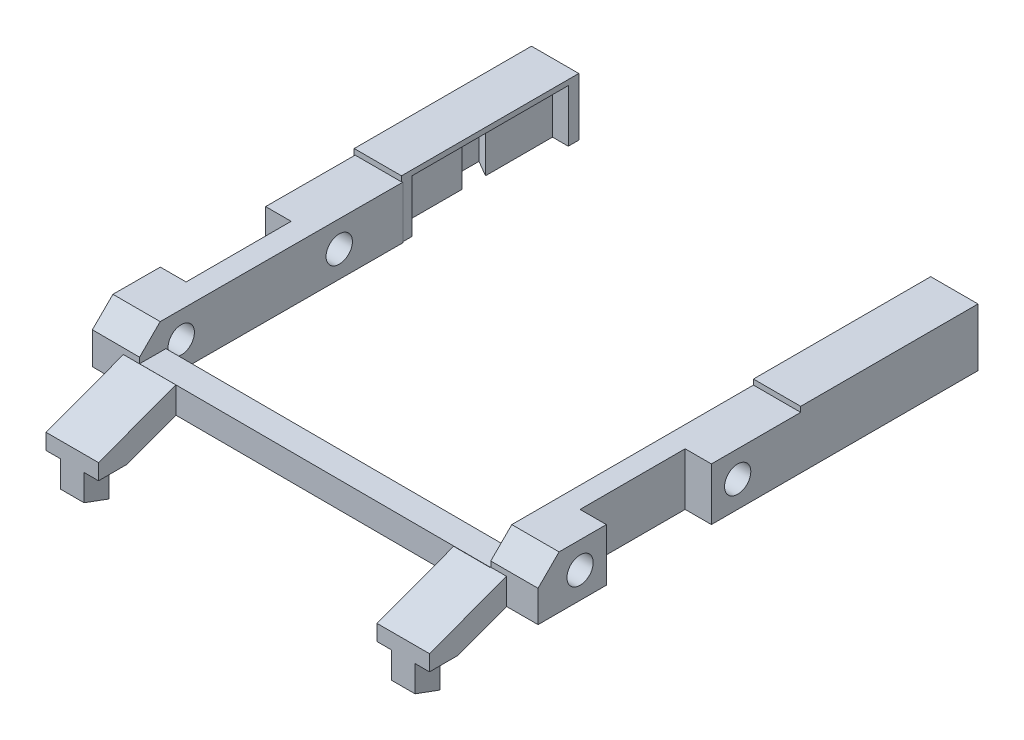
SolidWorks part; units mm, degrees
ref_plane "Front" through (0, 0, 0) normal (0, 0, 1) x (1, 0, 0)
ref_plane "Top" through (0, 0, 0) normal (0, 1, 0) x (1, 0, 0)
ref_plane "Right" through (0, 0, 0) normal (1, 0, 0) x (0, 0, -1)
sketch "Эскиз3" plane through (0, 0, 0) normal (0, 1, 0) x (1, 0, 0)
  line L0 (0, 14.0417) -> (0, -13.9583) construction
  line L1 (-30.3333, 0) -> (28.5833, 0) construction
  line L2 (-33.5, 14.875) -> (-33.5, 16.875)
  line L3 (-33.5, 16.875) -> (-42.5, 16.875)
  line L4 (-42.5, 16.875) -> (-42.5, -16.875)
  line L5 (-42.5, -16.875) -> (-33.5, -16.875)
  line L6 (-33.5, -16.875) -> (-33.5, -14.875)
  line L7 (-33.5, -14.875) -> (-36.5, -14.875)
  line L8 (-36.5, -14.875) -> (-36.5, 14.875)
  line L9 (-36.5, 14.875) -> (-33.5, 14.875)
  line L10 (30.3333, 0) -> (-28.5833, 0) construction
  line L11 (36.5, 14.875) -> (33.5, 14.875)
  line L12 (36.5, -14.875) -> (36.5, 14.875)
  line L13 (33.5, -14.875) -> (36.5, -14.875)
  line L14 (33.5, -16.875) -> (33.5, -14.875)
  line L15 (42.5, -16.875) -> (33.5, -16.875)
  line L16 (42.5, 16.875) -> (42.5, -16.875)
  line L17 (33.5, 16.875) -> (42.5, 16.875)
  line L18 (33.5, 14.875) -> (33.5, 16.875)
  dimension "D1" = 2
  dimension "D2" = 3
  dimension "D3" = 6
  dimension "D4" = 29.75
  dimension "D5" = 73
extrude "Бобышка-Вытянуть3" add sketch "Эскиз3" against normal blind 10
sketch "Эскиз4" plane through (0, 0, 0) normal (0, 1, 0) x (1, 0, 0)
  line L0 (-36.5, 2.125) -> (-39.5, 3.875)
  line L1 (-36.5, -14.875) -> (-36.5, 14.875) construction
  line L2 (-39.5, 3.875) -> (-39.5, -4.125)
  line L3 (-39.5, -4.125) -> (-36.5, -2.375)
  line L4 (-36.5, -2.375) -> (-36.5, 2.125)
  line L5 (0, 0) -> (0, 16.6208) construction
  line L6 (36.5, -2.375) -> (36.5, 2.125)
  line L7 (39.5, -4.125) -> (36.5, -2.375)
  line L8 (39.5, 3.875) -> (39.5, -4.125)
  line L9 (36.5, 2.125) -> (39.5, 3.875)
  line L10 (-36.5, 14.875) -> (-33.5, 14.875) construction
  point P13 (-36.5, -0.125)
  dimension "D1" = 4.5
  dimension "D2" = 8
  dimension "D3" = 3
  dimension "D4" = 15
extrude "Вырез-Вытянуть1" cut sketch "Эскиз4" against normal up to surface (10 mm away) up to face at (-36.5, -10, 0)
sketch "Эскиз5" plane through (0, 0, 0) normal (0, 1, 0) x (1, 0, 0)
  line L0 (-42.5, 16.875) -> (-42.5, -16.875) construction
  line L1 (-42.5, 16.875) -> (-33.5, 16.875)
  line L2 (-42.5, 16.875) -> (-42.5, -16.875)
  line L3 (-42.5, -16.875) -> (-33.5, -16.875)
  line L4 (-33.5, 16.875) -> (-33.5, -16.875)
  line L5 (-33.5, 16.875) -> (-42.5, 16.875) construction
  line L7 (33.5, 16.875) -> (42.5, 16.875)
  line L8 (33.5, 16.875) -> (33.5, -16.875)
  line L9 (33.5, -16.875) -> (42.5, -16.875)
  line L10 (42.5, 16.875) -> (42.5, -16.875)
extrude "Бобышка-Вытянуть4" add sketch "Эскиз5" along normal blind 1
sketch "Эскиз6" plane through (0, 1, 0) normal (0, 1, 0) x (1, 0, 0)
  line L0 (0.13, 14.875) -> (0, -90.9192) construction
  line L1 (26.8, 14.875) -> (-26.54, 14.875) construction
  line L2 (-8.5, -90.9192) -> (8.5, -90.9192) construction
  line L3 (-42.4408, -66.7706) -> (-33.4408, -66.7927)
  line L4 (42.5, -16.875) -> (33.5, -16.875)
  line L5 (42.5, -16.875) -> (42.5, -66.875)
  line L6 (42.5, -66.875) -> (33.5, -66.875)
  line L7 (33.5, -16.875) -> (33.5, -66.875)
  line L8 (-33.3179, -16.7929) -> (-33.4408, -66.7927)
  line L9 (-42.3179, -16.7708) -> (-42.4408, -66.7706)
  line L10 (-42.3179, -16.7708) -> (-33.3179, -16.7929)
  dimension "D1" = 50
extrude "Бобышка-Вытянуть5" add sketch "Эскиз6" against normal blind 10 from offset 1 offset against normal yes
sketch "Эскиз7" plane through (42.5, 0, 0) normal (1, 0, 0) x (0, 0, -1)
  line L0 (-62.875, 0) -> (-66.875, -4)
  line L1 (-66.875, 0) -> (-16.875, 0) construction
  line L2 (-66.875, -10) -> (-66.875, 0) construction
  line L3 (-66.875, -4) -> (-66.875, 0)
  line L4 (-66.875, 0) -> (-62.875, 0)
  dimension "D1" = 4
extrude "Вырез-Вытянуть2" cut sketch "Эскиз7" against normal through all
sketch "Эскиз8" plane through (-33.2765, 0, -0.0818) normal (1, 0, 0.0025) x (0.0025, 0, -1)
  line L1 (-66.8747, -10) -> (-61.8747, -10)
  line L2 (-66.8747, -10) -> (-66.8747, -5)
  line L3 (-66.8747, -5) -> (-61.8747, -5)
  line L4 (-61.8747, -10) -> (-61.8747, -5)
  dimension "D1" = 5
extrude "Бобышка-Вытянуть6" add sketch "Эскиз8" along normal up to surface (66.941 mm away)
sketch "Эскиз9" plane through (-26.5, 0, 0) normal (1, 0, 0) x (0, 0, -1)
  line L0 (-81.544, -13.4437) -> (-81.544, -10.4437)
  line L1 (-81.544, -10.4437) -> (-66.8098, -5)
  line L2 (-76.1307, -13.4437) -> (-66.8098, -10)
  line L3 (-76.1307, -13.4437) -> (-81.544, -13.4437)
  line L4 (-66.8098, -10) -> (-66.8098, -5)
  line L5 (-66.9573, -5) -> (-66.7927, -5) construction
  dimension "D1" = 3
extrude "Бобышка-Вытянуть7" add sketch "Эскиз9" against normal up to surface (10 mm away) separate body
sketch "Эскиз10" plane through (36.5, 0, 0) normal (1, 0, 0) x (0, 0, -1)
  line L0 (-81.544, -13.4437) -> (-81.544, -10.4437)
  line L1 (-81.544, -10.4437) -> (-66.8098, -5)
  line L2 (-76.1307, -13.4437) -> (-66.8098, -10)
  line L3 (-76.1307, -13.4437) -> (-81.544, -13.4437)
  line L4 (-66.8098, -10) -> (-66.8098, -5)
extrude "Бобышка-Вытянуть8" add sketch "Эскиз10" against normal up to surface (10 mm away)
sketch "Эскиз11" plane through (0, -13.4437, 0) normal (0, -1, 0) x (1, 0, 0)
  line L0 (-33.75, 81.544) -> (-35.5, 78.544)
  line L1 (-35.5, 78.544) -> (-27.5, 78.544)
  line L2 (-27.5, 78.544) -> (-29.25, 81.544)
  line L3 (-29.25, 81.544) -> (-33.75, 81.544)
  line L4 (27.5, 78.544) -> (35.5, 78.544)
  line L5 (35.5, 78.544) -> (33.75, 81.544)
  line L6 (33.75, 81.544) -> (29.25, 81.544)
  line L7 (29.25, 81.544) -> (27.5, 78.544)
extrude "Бобышка-Вытянуть9" add sketch "Эскиз11" along normal blind 5
sketch "Эскиз12" plane through (0, 0, 0) normal (0, 1, 0) x (1, 0, 0)
  line L0 (42.5, -62.875) -> (42.5, -16.875) construction
  line L1 (42.5, -53.875) -> (37.5, -53.875)
  line L2 (42.5, -53.875) -> (42.5, -33.875)
  line L3 (42.5, -33.875) -> (37.5, -33.875)
  line L4 (37.5, -53.875) -> (37.5, -33.875)
  line L5 (33.5, -62.875) -> (42.5, -62.875) construction
  line L6 (0, -119.6393) -> (0, 55.9849) construction
  line L7 (-42.5, -33.875) -> (-37.5, -33.875)
  line L8 (-42.5, -53.875) -> (-42.5, -33.875)
  line L9 (-37.5, -53.875) -> (-37.5, -33.875)
  line L10 (-42.5, -53.875) -> (-37.5, -53.875)
  dimension "D1" = 20
  dimension "D2" = 9
  dimension "D3" = 5
extrude "Вырез-Вытянуть3" cut sketch "Эскиз12" against normal up to surface (10 mm away) up to face at (0.1532, -10, 16.3971)
sketch "Эскиз13" plane through (42.5, 0, 0) normal (1, 0, 0) x (0, 0, -1)
  line L0 (-53.875, -10) -> (-53.875, 0) construction
  line L1 (-33.875, -10) -> (-33.875, 0) construction
  circle A0 centre (-58.875, -5) radius 2.5
  circle A1 centre (-28.875, -5) radius 2.5
  point P2 (-53.875, -5)
  dimension "D1" = 5
  dimension "D4" = 5
  dimension "D2" = 5
  dimension "D3" = 5
extrude "Вырез-Вытянуть4" cut sketch "Эскиз13" against normal through all
